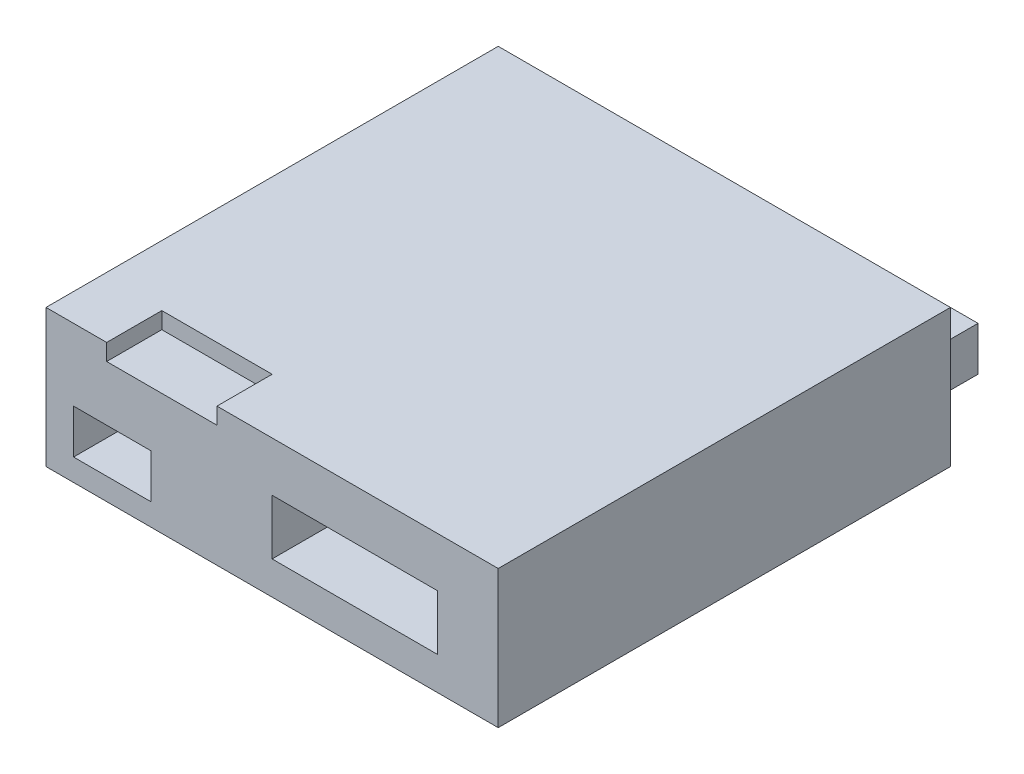
SolidWorks part; units mm, degrees
ref_plane "Front Plane" through (0, 0, 0) normal (0, 0, 1) x (1, 0, 0)
ref_plane "Top Plane" through (0, 0, 0) normal (0, 1, 0) x (1, 0, 0)
ref_plane "Right Plane" through (0, 0, 0) normal (1, 0, 0) x (0, 0, -1)
sketch "Sketch1" plane through (0, 0, 0) normal (0, 1, 0) x (1, 0, 0)
  line L1 (0, 0) -> (41, 0)
  line L2 (0, 0) -> (0, 41)
  line L3 (0, 41) -> (41, 41)
  line L4 (41, 0) -> (41, 41)
  dimension "D1" = 41
  dimension "D2" = 41
extrude "Boss-Extrude1" add sketch "Sketch1" along normal blind 12.5
sketch "Sketch2" plane through (0, 0, 0) normal (0, 0, 1) x (1, 0, 0)
  line L0 (0, 12.5) -> (0, 0) construction
  line L1 (5.5, 12.5) -> (15.5, 12.5)
  line L2 (5.5, 12.5) -> (5.5, 11)
  line L3 (5.5, 11) -> (15.5, 11)
  line L4 (15.5, 12.5) -> (15.5, 11)
  line L5 (0, 12.5) -> (41, 12.5) construction
  dimension "D1" = 10
  dimension "D2" = 5.5
  dimension "D3" = 1.5
extrude "Cut-Extrude1" cut sketch "Sketch2" against normal blind 5
sketch "Sketch3" plane through (0, 0, 0) normal (0, 0, 1) x (1, 0, 0)
  line L0 (0, 12.5) -> (0, 0) construction
  line L1 (2.5, 6) -> (9.5, 6)
  line L2 (2.5, 6) -> (2.5, 2)
  line L3 (2.5, 2) -> (9.5, 2)
  line L4 (9.5, 6) -> (9.5, 2)
  line L5 (0, 0) -> (41, 0) construction
  dimension "D1" = 2.5
  dimension "D2" = 7
  dimension "D3" = 4
  dimension "D4" = 2
extrude "Cut-Extrude2" cut sketch "Sketch3" against normal blind 5
sketch "Sketch4" plane through (0, 0, 0) normal (0, 0, 1) x (1, 0, 0)
  line L0 (0, 0) -> (41, 0) construction
  line L1 (20.5, 8) -> (35.5, 8)
  line L2 (20.5, 8) -> (20.5, 3)
  line L3 (20.5, 3) -> (35.5, 3)
  line L4 (35.5, 8) -> (35.5, 3)
  line L5 (41, 12.5) -> (41, 0) construction
  dimension "D1" = 15
  dimension "D2" = 5
  dimension "D3" = 3
  dimension "D4" = 5.5
extrude "Cut-Extrude3" cut sketch "Sketch4" against normal blind 5
sketch "Sketch5" plane through (0, 0, -41) normal (0, 0, -1) x (-1, 0, 0)
  line L1 (-27.5, 7.5) -> (-38.5, 7.5)
  line L2 (-27.5, 7.5) -> (-27.5, 3.5)
  line L3 (-27.5, 3.5) -> (-38.5, 3.5)
  line L4 (-38.5, 7.5) -> (-38.5, 3.5)
  line L6 (-41, 12.5) -> (-41, 0) construction
  line L7 (-41, 12.5) -> (0, 12.5) construction
  dimension "D1" = 2.5
  dimension "D2" = 11
  dimension "D3" = 5
  dimension "D4" = 4
extrude "Boss-Extrude2" add sketch "Sketch5" along normal blind 5
